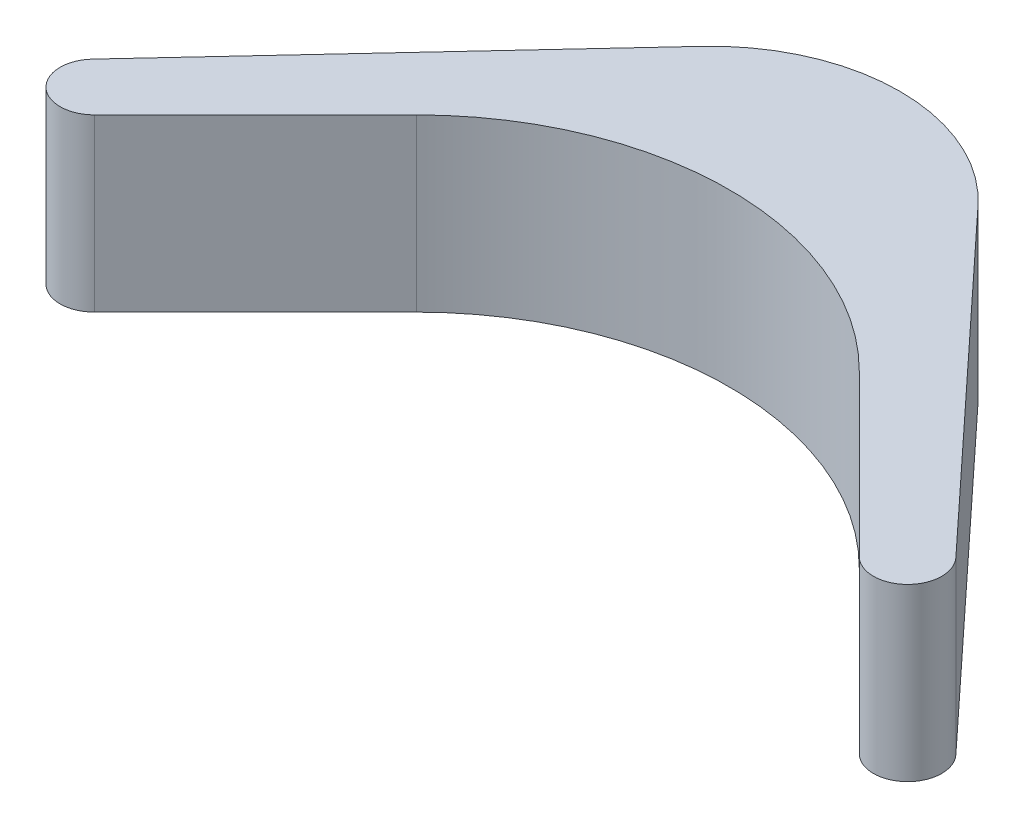
SolidWorks part; units mm, degrees
ref_plane "Front Plane" through (0, 0, 0) normal (0, 0, 1) x (1, 0, 0)
ref_plane "Top Plane" through (0, 0, 0) normal (0, 1, 0) x (1, 0, 0)
ref_plane "Right Plane" through (0, 0, 0) normal (1, 0, 0) x (0, 0, -1)
sketch "Sketch1" plane through (0, 0, 0) normal (0, 1, 0) x (1, 0, 0)
  line L0 (-19.4454, 19.4454) -> (-33.5876, 5.3033)
  line L1 (0, 0) -> (115.0741, 0) construction
  line L3 (19.4454, 19.4454) -> (33.5876, 5.3033)
  line L4 (-37.9058, 9.4675) -> (-12.1319, 37.185)
  line L5 (12.1319, 37.185) -> (37.9058, 9.4675)
  arc A0 (19.4454, 19.4454) -> (-19.4454, 19.4454) centre (0, 0) ccw
  arc A1 (-37.9058, 9.4675) -> (-33.5876, 5.3033) centre (-35.7089, 7.4246) ccw
  arc A2 (33.5876, 5.3033) -> (37.9058, 9.4675) centre (35.7089, 7.4246) ccw
  arc A4 (12.1319, 37.185) -> (-12.1319, 37.185) centre (0, 25.9037) ccw
  arc A5 (35.0414, 0) -> (41.5685, 12.8286) centre (0, 25.9037) ccw
  point P1 (-61.873, -12.3932)
  point P3 (-61.873, -12.3932)
  point P13 (-61.873, -12.3932)
  point P14 (-61.873, -12.3932)
  point P15 (-61.873, -12.3932)
  point P18 (0, 0)
  point P19 (0, 14.1747)
  dimension "D1" = 55
  dimension "D5" = 3
  dimension "D2" = 45
  dimension "D3" = 20
  dimension "D4" = 20
  dimension "D6" = 71.4178
extrude "Boss-Extrude1" add sketch "Sketch1" along normal blind 15
